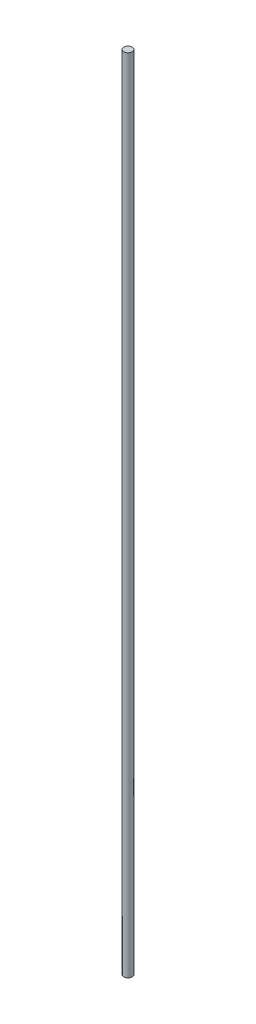
SolidWorks part; units mm, degrees
ref_plane "Front Plane" through (0, 0, 0) normal (0, 0, 1) x (1, 0, 0)
ref_plane "Top Plane" through (0, 0, 0) normal (0, 1, 0) x (1, 0, 0)
ref_plane "Right Plane" through (0, 0, 0) normal (1, 0, 0) x (0, 0, -1)
sketch "Sketch1" plane through (0, 0, 0) normal (0, 1, 0) x (1, 0, 0)
  circle A0 centre (0, 0) radius 0.7937
  dimension "D1" = 1.5875
extrude "Boss-Extrude1" add sketch "Sketch1" along normal blind 152.4
